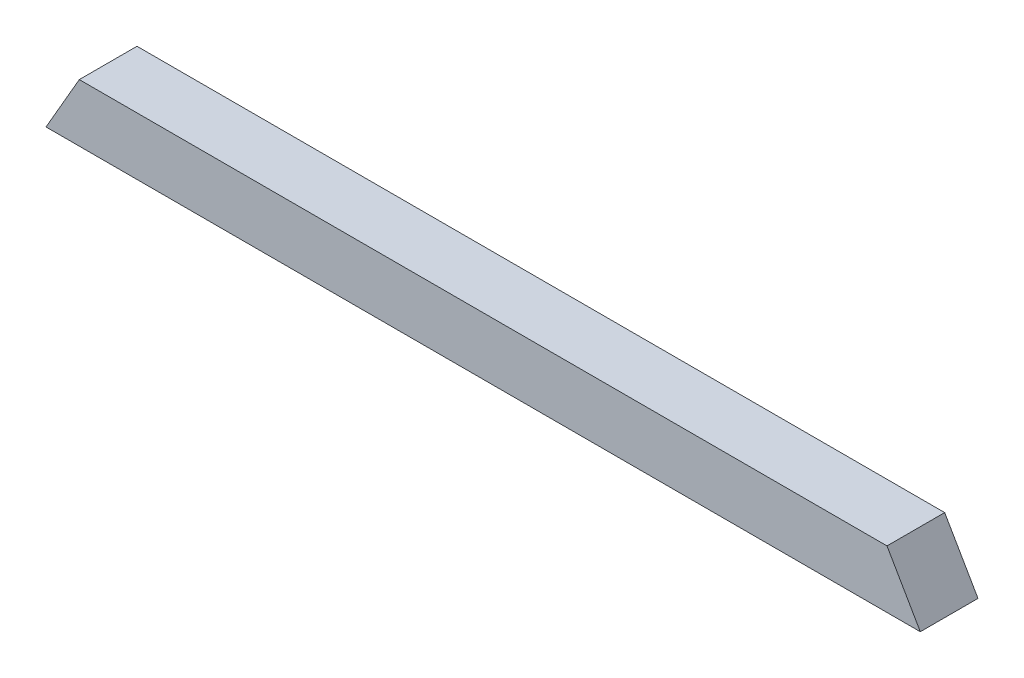
SolidWorks part; units mm, degrees
ref_plane "Front Plane" through (0, 0, 0) normal (0, 0, 1) x (1, 0, 0)
ref_plane "Top Plane" through (0, 0, 0) normal (0, 1, 0) x (1, 0, 0)
ref_plane "Right Plane" through (0, 0, 0) normal (1, 0, 0) x (0, 0, -1)
sketch "Sketch1" plane through (0, 0, 0) normal (0, 0, 1) x (1, 0, 0)
  line L0 (-140, 0) -> (140, 0)
  line L1 (0, 0) -> (0, -20) construction
  line L2 (-140, 0) -> (-159.4798, -33.7401) construction
  line L3 (140, 0) -> (152.5705, -21.7727) construction
  line L4 (-151.547, -20) -> (151.547, -20)
  line L5 (-140, 0) -> (-151.547, -20)
  line L6 (140, 0) -> (151.547, -20)
  point P4 (0, 0)
  point P6 (145.7735, -10)
  point P11 (0, -20)
  dimension "D1" = 280
  dimension "D2" = 120
  dimension "D3" = 120
  dimension "D4" = 20
  dimension "D5" = 10
extrude "Boss-Extrude2" add sketch "Sketch1" along normal blind 20
